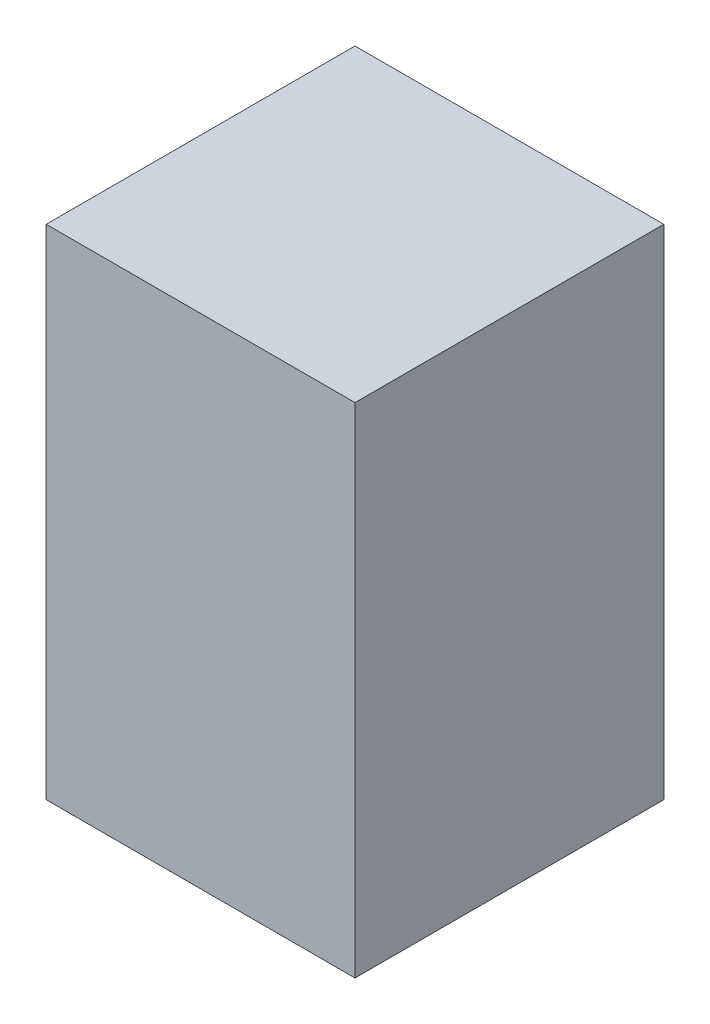
SolidWorks part; units mm, degrees
ref_plane "Front Plane" through (0, 0, 0) normal (0, 0, 1) x (1, 0, 0)
ref_plane "Top Plane" through (0, 0, 0) normal (0, 1, 0) x (1, 0, 0)
ref_plane "Right Plane" through (0, 0, 0) normal (1, 0, 0) x (0, 0, -1)
sketch "Sketch1" plane through (0, 0, 0) normal (0, 1, 0) x (1, 0, 0)
  line L1 (-21.1, -21.1) -> (21.1, -21.1)
  line L2 (-21.1, -21.1) -> (-21.1, 21.1)
  line L3 (-21.1, 21.1) -> (21.1, 21.1)
  line L4 (21.1, -21.1) -> (21.1, 21.1)
  line L5 (-21.1, -21.1) -> (21.1, 21.1) construction
  line L6 (-21.1, 21.1) -> (21.1, -21.1) construction
  point P0 (0, 0)
  dimension "D1" = 42.2
extrude "Boss-Extrude1" add sketch "Sketch1" along normal blind 68.1
sketch "Sketch2" plane through (0, 0, 0) normal (0, -1, 0) x (1, 0, 0)
  circle A0 centre (0, 0) radius 11
  dimension "D1" = 22
extrude "Boss-Extrude2" add sketch "Sketch2" along normal blind 1.8
